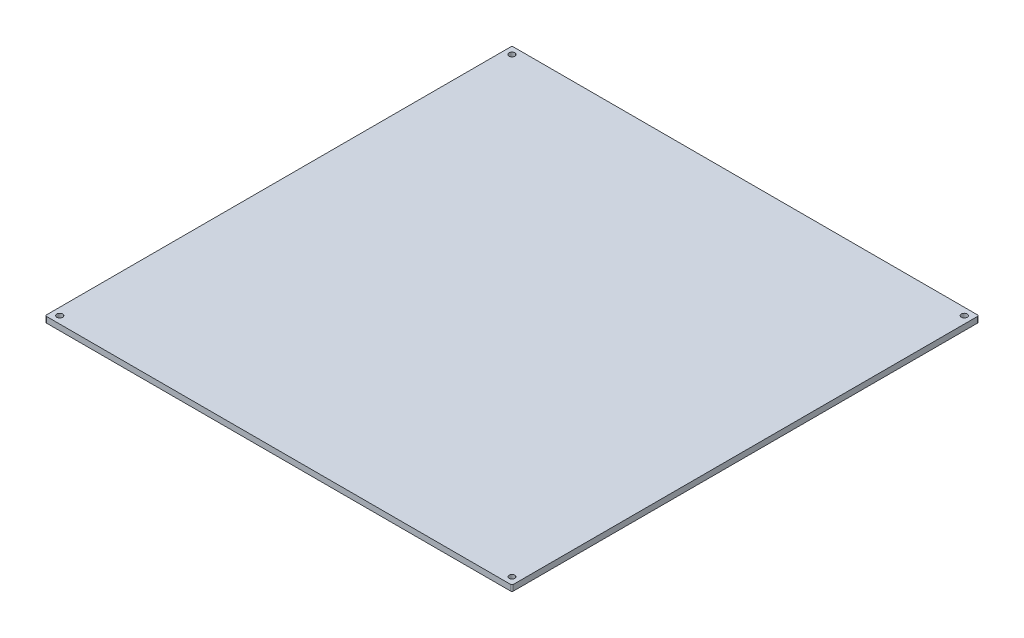
SolidWorks part; units mm, degrees
ref_plane "Front" through (0, 0, 0) normal (0, 0, 1) x (1, 0, 0)
ref_plane "Top" through (0, 0, 0) normal (0, 1, 0) x (1, 0, 0)
ref_plane "Right" through (0, 0, 0) normal (1, 0, 0) x (0, 0, -1)
sketch "Эскиз1" plane through (0, 0, 0) normal (0, 1, 0) x (1, 0, 0)
  line L1 (-159, -160) -> (159, -160)
  line L2 (-160, -159) -> (-160, 159)
  line L3 (-159, 160) -> (159, 160)
  line L4 (160, -159) -> (160, 159)
  line L5 (-160, -160) -> (160, 160) construction
  line L6 (-160, 160) -> (160, -160) construction
  line L7 (-155, -155) -> (155, -155) construction
  line L8 (-155, -155) -> (-155, 155) construction
  line L9 (-155, 155) -> (155, 155) construction
  line L10 (155, -155) -> (155, 155) construction
  line L11 (-155, -155) -> (155, 155) construction
  line L12 (-155, 155) -> (155, -155) construction
  circle A0 centre (-155, 155) radius 2
  circle A1 centre (155, 155) radius 2
  circle A2 centre (-155, -155) radius 2
  circle A3 centre (155, -155) radius 2
  arc A4 (-159, -160) -> (-160, -159) centre (-159, -159) cw
  arc A5 (159, -160) -> (160, -159) centre (159, -159) ccw
  arc A6 (159, 160) -> (160, 159) centre (159, 159) cw
  arc A7 (-160, 159) -> (-159, 160) centre (-159, 159) cw
  point P0 (0, 0)
  point P6 (0, 0)
  dimension "D5" = 1
  dimension "D1" = 320
  dimension "D2" = 320
  dimension "D3" = 310
  dimension "D4" = 310
extrude "Бобышка-Вытянуть1" add sketch "Эскиз1" along normal blind 4
sketch "Эскиз2" plane through (0, 0, 0) normal (0, -1, 0) x (1, 0, 0)
  line L1 (-155, 155) -> (155, 155)
  line L2 (-155, 155) -> (-155, -155)
  line L3 (-155, -155) -> (155, -155)
  line L4 (155, 155) -> (155, -155)
  line L5 (-155, 155) -> (155, -155) construction
  line L6 (-155, -155) -> (155, 155) construction
  point P0 (0, 0)
  dimension "D1" = 310
  dimension "D2" = 310
extrude "Бобышка-Вытянуть2" [suppressed] add sketch "Эскиз2" along normal blind 0.5
